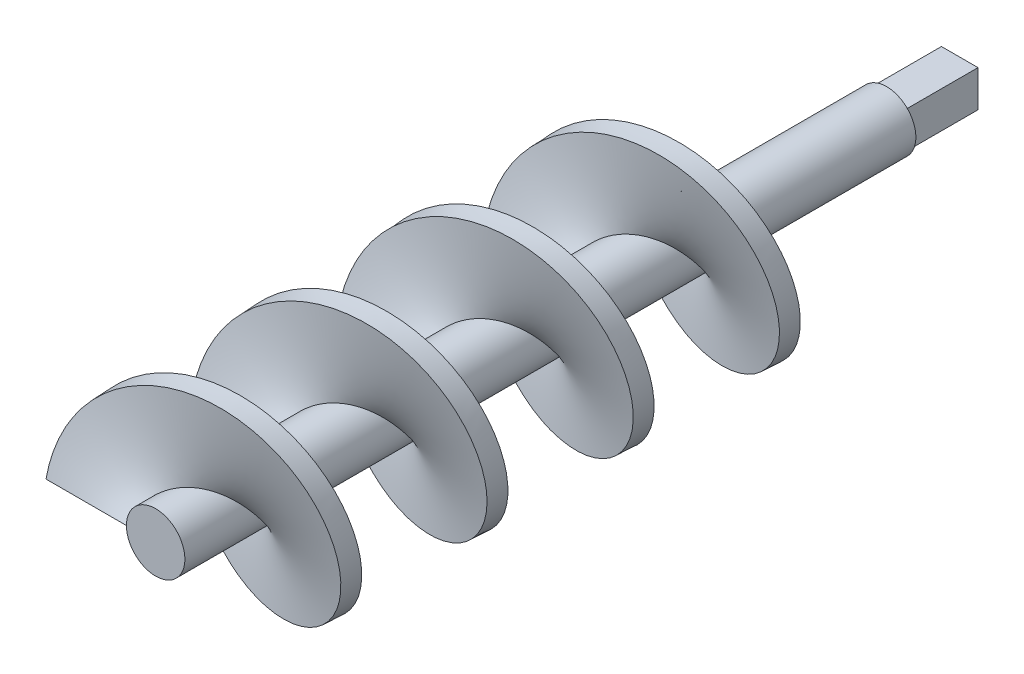
SolidWorks part; units mm, degrees
ref_plane "Front Plane" through (0, 0, 0) normal (0, 0, 1) x (1, 0, 0)
ref_plane "Top Plane" through (0, 0, 0) normal (0, 1, 0) x (1, 0, 0)
ref_plane "Right Plane" through (0, 0, 0) normal (1, 0, 0) x (0, 0, -1)
sketch "Sketch1" plane through (0, 0, 0) normal (0, 0, 1) x (1, 0, 0)
  circle A0 centre (0, 0) radius 2
  dimension "D1" = 4
extrude "Boss-Extrude1" add sketch "Sketch1" along normal blind 55
sketch "Sketch7" plane through (0, 0, 55) normal (0, 0, 1) x (1, 0, 0)
  circle A0 centre (0, 0) radius 2 construction
  circle A1 centre (0, 0) radius 2
curve "Helix/Spiral1" pitch 10 height 40 turns 4
ref_plane "Plane1" through (-2, 0, 55) normal (0, 0.7825, -0.6227) x (-1, 0, 0)
sketch "Sketch8" plane through (-2, 0, 55) normal (0, 0.7825, -0.6227) x (-1, 0, 0)
  line L1 (0, 0) -> (5.5, 0)
  line L2 (0, 0) -> (0, -1.5)
  line L3 (0, -1.5) -> (5.5, -1.5)
  line L4 (5.5, 0) -> (5.5, -1.5)
  dimension "D1" = 5.5
  dimension "D2" = 1.5
sweep "Sweep1" add profiles "Sketch8" path "Helix/Spiral1"
sketch "Sketch9" plane through (0, 0, 0) normal (0, 0, -1) x (-1, 0, 0)
  line L0 (-2.25, -2.25) -> (2.25, -2.25)
  line L1 (-1.25, 1.25) -> (1.25, 1.25)
  line L2 (-1.25, 1.25) -> (-1.25, -1.25)
  line L3 (-1.25, -1.25) -> (1.25, -1.25)
  line L4 (1.25, 1.25) -> (1.25, -1.25)
  line L5 (-1.25, 1.25) -> (1.25, -1.25) construction
  line L6 (-1.25, -1.25) -> (1.25, 1.25) construction
  line L7 (2.25, 2.25) -> (2.25, -2.25)
  line L8 (-2.25, 2.25) -> (2.25, 2.25)
  line L9 (-2.25, 2.25) -> (-2.25, -2.25)
  point P0 (0, 0)
  dimension "D1" = 2.5
  dimension "D2" = 2.5
extrude "Cut-Extrude1" cut sketch "Sketch9" against normal blind 5
